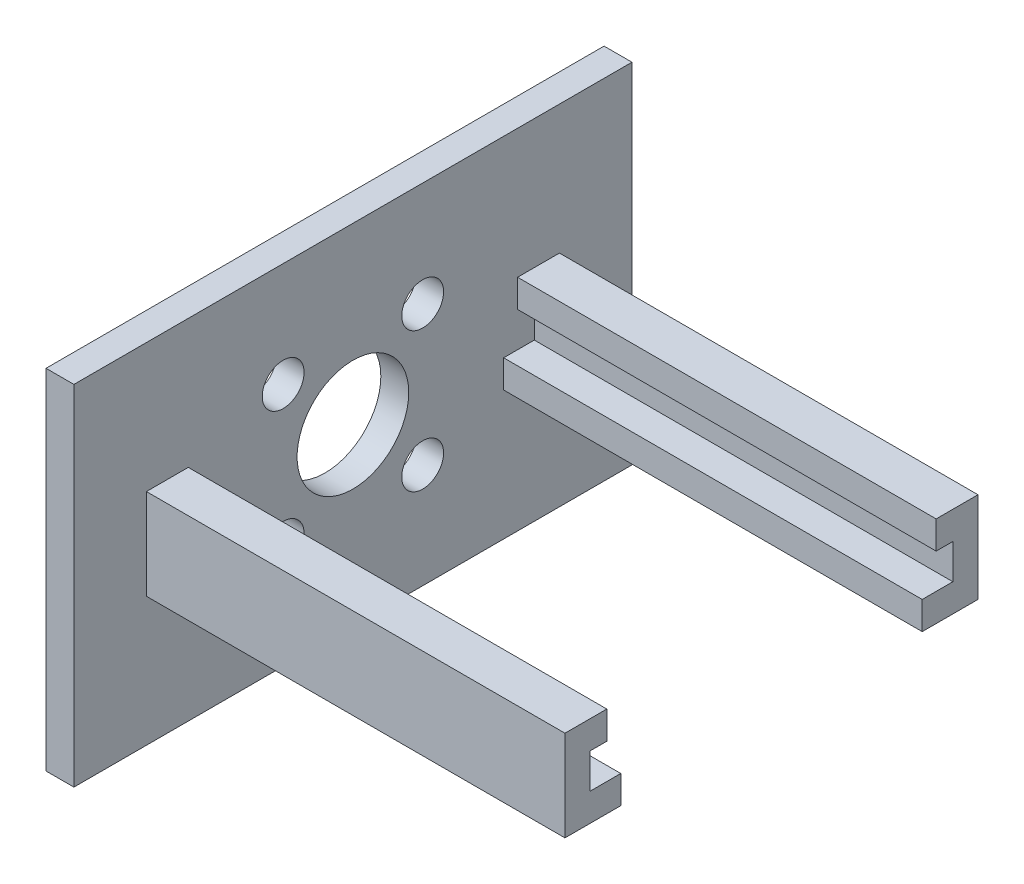
SolidWorks part; units mm, degrees
ref_plane "Front Plane" through (0, 0, 0) normal (0, 0, 1) x (1, 0, 0)
ref_plane "Top Plane" through (0, 0, 0) normal (0, 1, 0) x (1, 0, 0)
ref_plane "Right Plane" through (0, 0, 0) normal (1, 0, 0) x (0, 0, -1)
sketch "Sketch1" plane through (0, 0, 0) normal (1, 0, 0) x (0, 0, -1)
  line L1 (-20, 12.5) -> (20, 12.5)
  line L2 (-20, 12.5) -> (-20, -12.5)
  line L3 (-20, -12.5) -> (20, -12.5)
  line L4 (20, 12.5) -> (20, -12.5)
  dimension "D2" = 25
  dimension "D3" = 40
extrude "Boss-Extrude1" add sketch "Sketch1" along normal blind 1
sketch "Sketch2" plane through (1, 0, 0) normal (1, 0, 0) x (0, 0, -1)
  line L1 (-20, 12.5) -> (20, 12.5)
  line L2 (-20, 12.5) -> (-20, -12.5)
  line L3 (-20, -12.5) -> (20, -12.5)
  line L4 (20, 12.5) -> (20, -12.5)
extrude "Boss-Extrude2" add sketch "Sketch2" along normal blind 1
sketch "Sketch3" plane through (2, 0, 0) normal (1, 0, 0) x (0, 0, -1)
  line L1 (-12.5, -1.25) -> (12.5, -1.25) construction
  line L2 (-12.5, -1.25) -> (-12.5, 1.25) construction
  line L3 (-12.5, 1.25) -> (12.5, 1.25) construction
  line L4 (12.5, -1.25) -> (12.5, 1.25) construction
  line L5 (-12.5, -1.25) -> (12.5, 1.25) construction
  line L6 (-12.5, 1.25) -> (12.5, -1.25) construction
  line L7 (11.8027, 1.25) -> (11.8027, 3.25)
  line L8 (11.8027, 3.25) -> (14.8027, 3.25)
  line L9 (14.8027, 3.25) -> (14.8027, -3.25)
  line L10 (14.8027, -3.25) -> (10.8027, -3.25)
  line L11 (10.8027, -3.25) -> (10.8027, -1.25)
  line L12 (10.8027, -1.25) -> (13, -1.25)
  line L13 (13, -1.25) -> (13, 1.25)
  line L15 (13, 1.25) -> (11.8027, 1.25)
  line L16 (0, 0) -> (0, 5.6542) construction
  line L17 (-13, -1.25) -> (-13, 1.25)
  line L18 (-10.8027, -1.25) -> (-13, -1.25)
  line L19 (-10.8027, -3.25) -> (-10.8027, -1.25)
  line L20 (-14.8027, -3.25) -> (-10.8027, -3.25)
  line L21 (-14.8027, 3.25) -> (-14.8027, -3.25)
  line L22 (-11.8027, 3.25) -> (-14.8027, 3.25)
  line L23 (-11.8027, 1.25) -> (-11.8027, 3.25)
  line L24 (-13, 1.25) -> (-11.8027, 1.25)
  point P0 (0, 0)
  dimension "D1" = 2.5
  dimension "D2" = 25
  dimension "D3" = 2.1973
  dimension "D4" = 2
  dimension "D5" = 3
  dimension "D6" = 2
  dimension "D7" = 0.5
  dimension "D8" = 1.8027
extrude "Boss-Extrude3" add sketch "Sketch3" along normal blind 30
sketch "Sketch5" plane through (2, 0, 0) normal (1, 0, 0) x (0, 0, -1)
  line L1 (-5, -5) -> (5, -5) construction
  line L2 (-5, -5) -> (-5, 5) construction
  line L3 (-5, 5) -> (5, 5) construction
  line L4 (5, -5) -> (5, 5) construction
  line L5 (-5, -5) -> (5, 5) construction
  line L6 (-5, 5) -> (5, -5) construction
  circle A0 centre (5, 5) radius 1.5
  circle A1 centre (5, -5) radius 1.5
  circle A2 centre (-5, -5) radius 1.5
  circle A3 centre (-5, 5) radius 1.5
  circle A4 centre (0, 0) radius 4
  point P0 (0, 0)
  dimension "D2" = 3
  dimension "D3" = 3
  dimension "D4" = 3
  dimension "D5" = 3
  dimension "D6" = 8
  dimension "D1" = 10
extrude "Cut-Extrude2" cut sketch "Sketch5" against normal blind 10
